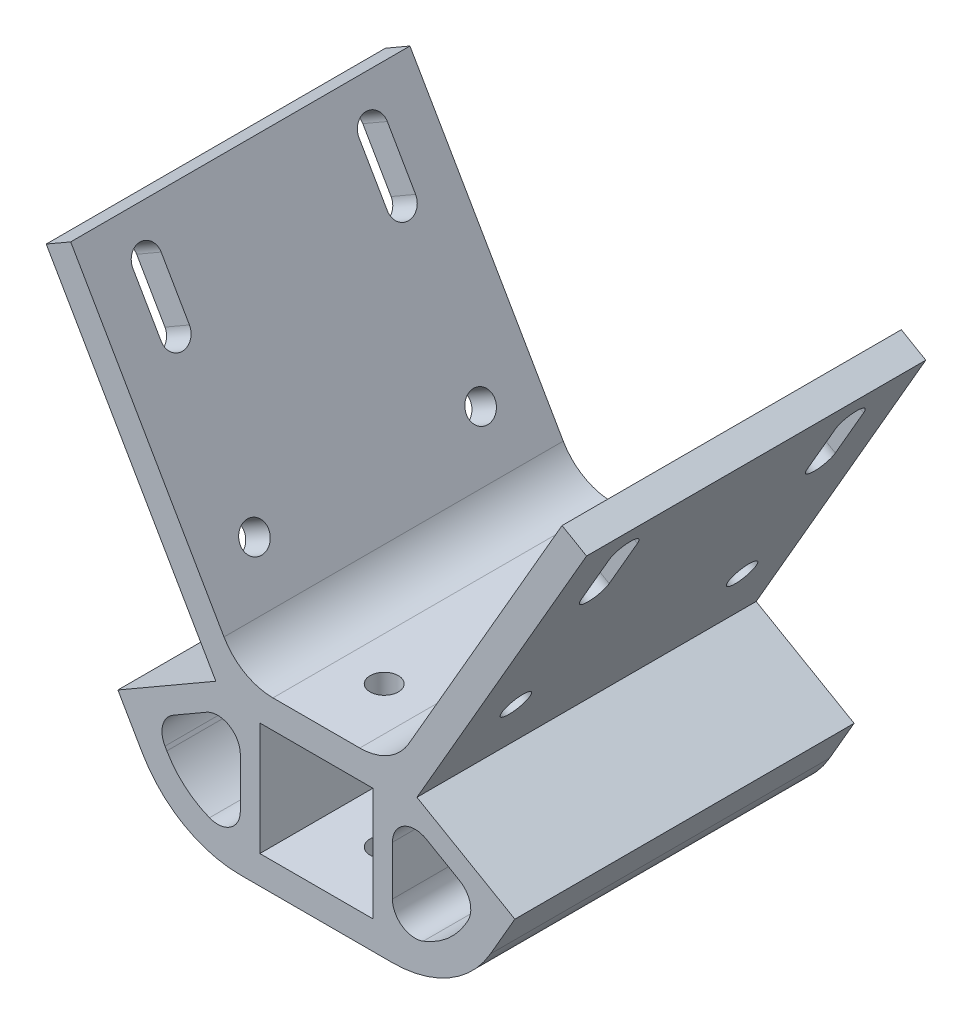
SolidWorks part; units mm, degrees
material "ABS generico"
ref_plane "Piano frontale" through (0, 0, 0) normal (0, 0, 1) x (1, 0, 0)
ref_plane "Piano superiore" through (0, 0, 0) normal (0, 1, 0) x (1, 0, 0)
ref_plane "Piano destro" through (0, 0, 0) normal (1, 0, 0) x (0, 0, -1)
sketch "Schizzo1" plane through (0, 0, 0) normal (0, 0, 1) x (1, 0, 0)
  line L0 (25, 0) -> (-25, 0)
  line L1 (-25, 0) -> (-35.1036, 17.5)
  line L2 (-35.1036, 17.5) -> (-17.7831, 27.5)
  line L3 (-17.7831, 27.5) -> (-47.7831, 79.4615)
  line L4 (-47.7831, 79.4615) -> (-43.453, 81.9615)
  line L5 (-10, 25) -> (10, 25)
  line L6 (-10, 25) -> (-10, 5)
  line L7 (-10, 5) -> (10, 5)
  line L8 (10, 25) -> (10, 5)
  line L9 (-10, 25) -> (10, 5) construction
  line L10 (-10, 5) -> (10, 25) construction
  line L11 (-43.453, 81.9615) -> (-13.453, 30)
  line L12 (-13.453, 30) -> (13.453, 30)
  line L13 (-17.7831, 27.5) -> (-13.453, 30) construction
  line L14 (0, 30) -> (0, 0) construction
  line L15 (25, 0) -> (35.1036, 17.5)
  line L16 (35.1036, 17.5) -> (17.7831, 27.5)
  line L17 (43.453, 81.9615) -> (13.453, 30)
  line L18 (47.7831, 79.4615) -> (43.453, 81.9615)
  line L19 (17.7831, 27.5) -> (47.7831, 79.4615)
  point P11 (0, 15)
  point P19 (0, 0)
  dimension "D6" = 5
  dimension "D1" = 25
  dimension "D2" = 120
  dimension "D3" = 5
  dimension "D4" = 60
  dimension "D5" = 20
  dimension "D7" = 20
  dimension "D8" = 20
  dimension "D9" = 15
extrude "Estrusione-Estrusione1" add sketch "Schizzo1" along normal blind 60
fillet "Raccordo1" radius 20 2 edges at (25, 0, 30) (-25, 0, 30)
sketch "Schizzo8" plane through (-1.4295, -0.8253, 0) normal (-0.866, -0.5, 0) x (0, 0, 1)
  line L0 (10, 92.7073) -> (10, 32.7073) construction
  line L1 (60, 92.7073) -> (0, 92.7073) construction
  line L2 (60, 32.7073) -> (0, 32.7073) construction
  line L3 (30, 92.7073) -> (30, 32.7073) construction
  line L4 (10, 85.7073) -> (10, 75.7073) construction
  line L5 (0, 92.7073) -> (0, 32.7073) construction
  line L6 (60, 32.7073) -> (0, 32.7073) construction
  line L7 (50, 92.7073) -> (50, 32.7073) construction
  line L9 (12.5, 85.7073) -> (12.5, 75.7073)
  line L10 (7.5, 85.7073) -> (7.5, 75.7073)
  line L11 (50, 85.7073) -> (50, 75.7073) construction
  line L12 (47.5, 85.7073) -> (47.5, 75.7073)
  line L13 (52.5, 85.7073) -> (52.5, 75.7073)
  arc A0 (12.5, 85.7073) -> (7.5, 85.7073) centre (10, 85.7073) ccw
  circle A1 centre (10, 47.7073) radius 2.5
  circle A2 centre (50, 47.7073) radius 2.5
  arc A3 (47.5, 85.7073) -> (52.5, 85.7073) centre (50, 85.7073) cw
  arc A4 (7.5, 75.7073) -> (12.5, 75.7073) centre (10, 75.7073) ccw
  arc A5 (52.5, 75.7073) -> (47.5, 75.7073) centre (50, 75.7073) cw
  point P22 (10, 80.7073)
  point P27 (50, 80.7073)
  dimension "D4" = 10
  dimension "D2" = 2.5
  dimension "D6" = 5
  dimension "D1" = 10
  dimension "D3" = 15
  dimension "D5" = 12
extrude "Taglio-Estrusione3" cut sketch "Schizzo8" against normal blind 5
mirror "Specchia1" about plane through (0, 0, 0) normal (1, 0, 0) of "Taglio-Estrusione3"
sketch "Schizzo10" plane through (0, 0, 0) normal (0, 0, -1) x (-1, 0, 0)
  line L1 (-28.7735, 16.5359) -> (-13.453, 25.3812)
  line L2 (-26.4434, 12.5) -> (-30.7735, 20)
  line L3 (-26.4434, 12.5) -> (-28.7735, 16.5359)
  line L4 (0, 30) -> (0, 0) construction
  line L5 (-13.453, 25.3812) -> (-13.453, 5)
  line L6 (-10, 5) -> (-10, 25) construction
  line L7 (-35.1036, 17.5) -> (-17.7831, 27.5) construction
  line L8 (-13.453, 30) -> (13.453, 30) construction
  line L9 (13.453, 25.3812) -> (13.453, 5)
  line L10 (26.4434, 12.5) -> (28.7735, 16.5359)
  line L11 (28.7735, 16.5359) -> (13.453, 25.3812)
  arc A1 (26.4434, 12.5) -> (13.453, 5) centre (13.453, 20) cw
  arc A2 (-26.4434, 12.5) -> (-13.453, 5) centre (-13.453, 20) ccw
  arc A3 (-26.4434, 12.5) -> (-13.453, 5) centre (-13.453, 20) ccw
  dimension "D2" = 4
  dimension "D1" = 5
extrude "Taglio-Estrusione4" cut sketch "Schizzo10" against normal through all
fillet "Raccordo2" radius 10 2 edges at (13.453, 30, 30) (-13.453, 30, 30)
fillet "Raccordo3" radius 4 6 edges at (-13.453, 5, 30) (-28.7735, 16.5359, 30) (28.7735, 16.5359, 30) (13.453, 5, 30) (13.453, 25.3812, 30) (-13.453, 25.3812, 30)
sketch "Schizzo11" plane through (0, 0, 0) normal (0, -1, 0) x (1, 0, 0)
  line L0 (0, 60) -> (0, 0) construction
  line L1 (-13.453, 60) -> (13.453, 60) construction
  circle A0 centre (0, 48) radius 2.5
  circle A1 centre (0, 12) radius 2.5
  point P9 (0, 30)
  dimension "D1" = 5
  dimension "D2" = 36
  dimension "D3" = 18
extrude "Taglio-Estrusione5" cut sketch "Schizzo11" against normal through all
